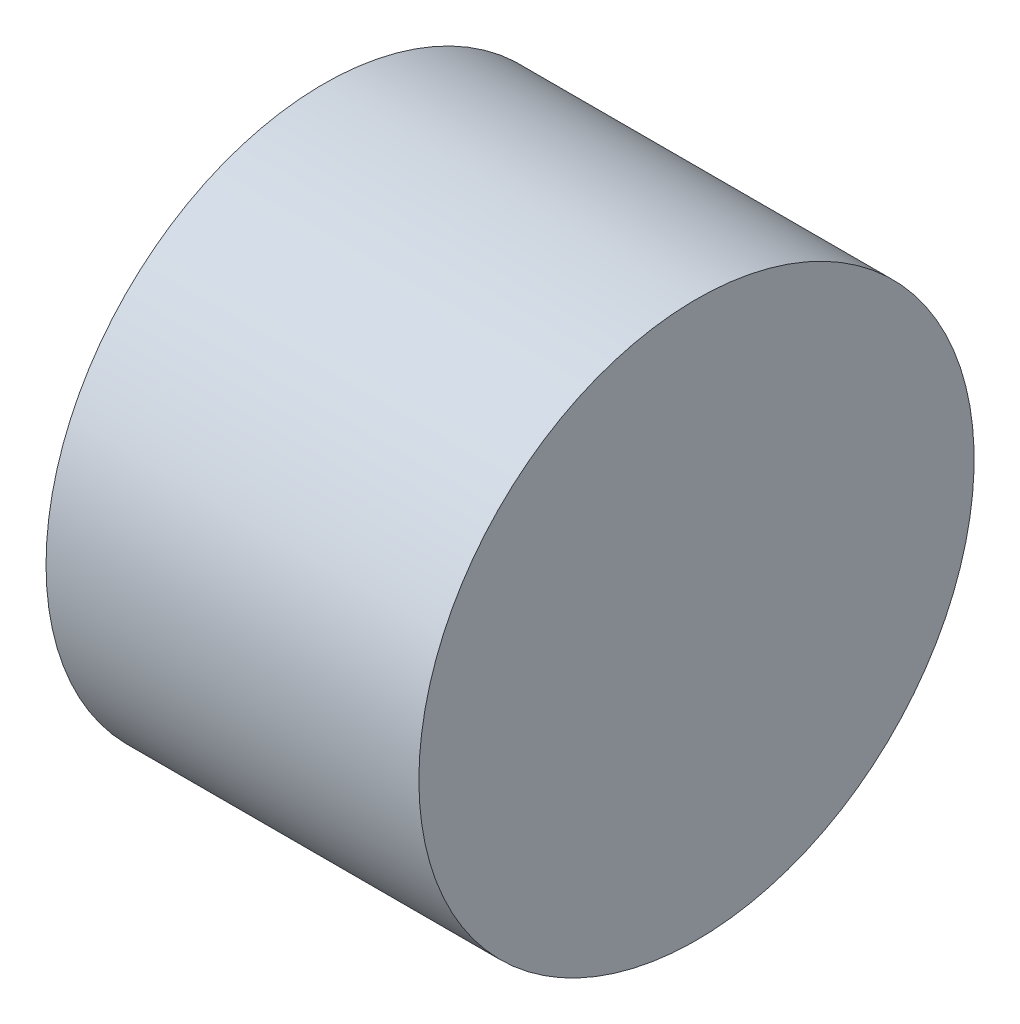
SolidWorks part; units mm, degrees
material "PTFE (general)"
ref_plane "Front" through (0, 0, 0) normal (0, 0, 1) x (1, 0, 0)
ref_plane "Top" through (0, 0, 0) normal (0, 1, 0) x (1, 0, 0)
ref_plane "Right" through (0, 0, 0) normal (1, 0, 0) x (0, 0, -1)
sketch "Sketch1" plane through (0, 0, 0) normal (0, 1, 0) x (1, 0, 0)
  line L0 (-27.6478, 0) -> (28.0532, 0) construction
  line L1 (17.5, 17.5) -> (-6, 17.5)
  line L2 (-6, 17.5) -> (-6, 10.3923)
  line L4 (17.5, 0) -> (17.5, 17.5)
  line L5 (-50, 0) -> (50, 0) construction
  line L6 (-6, 17.5) -> (-6, 10.3923) construction
  line L7 (0, -50) -> (0, 50) construction
  line L8 (-17.5, 0) -> (-17.5, -17.5) [skipped]
  line L11 (12, 0) -> (17.5, 0)
  line L13 (-6, -17.5) -> (17.5, -17.5) [skipped]
  arc A1 (12, 0) -> (-6, 10.3923) centre (0, 0) ccw
  dimension "D1" = 6
revolve "Revolve7" add sketch "Sketch1" angle 360 about L0
